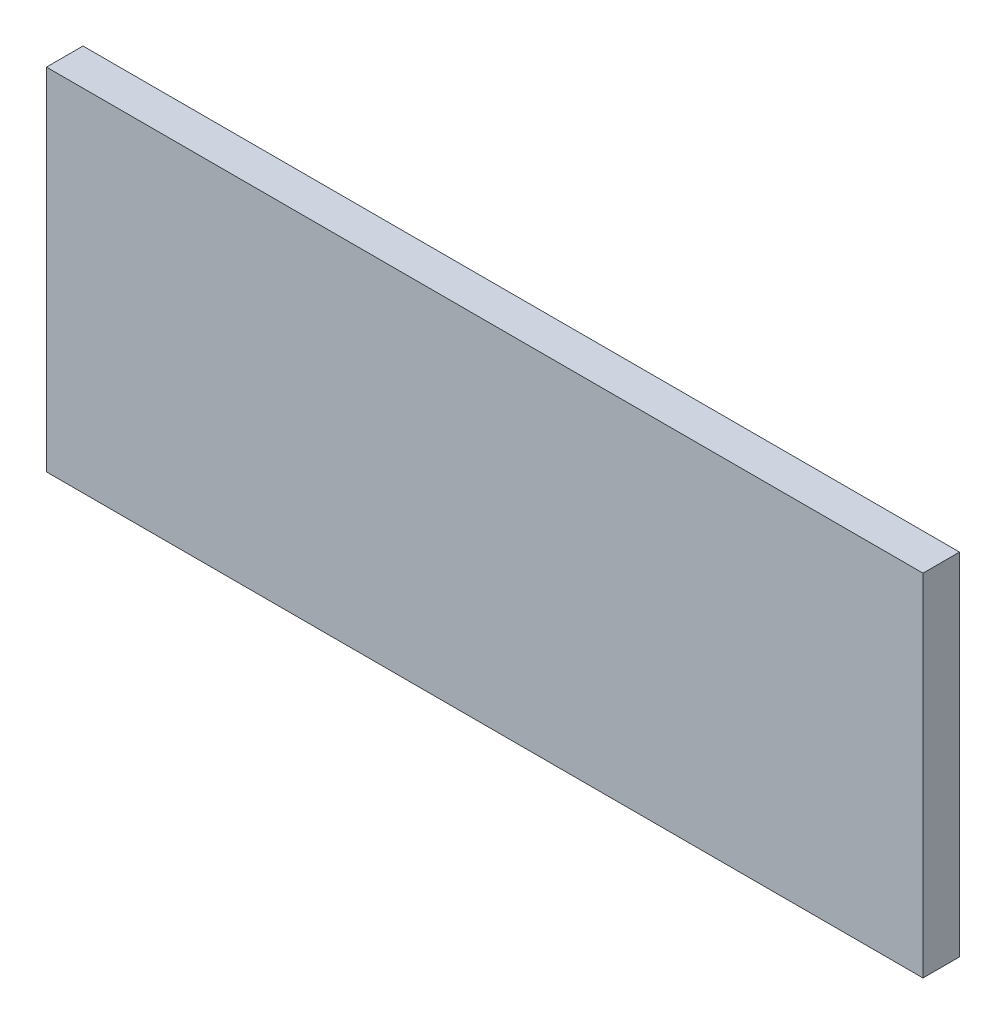
SolidWorks part; units mm, degrees
ref_plane "Front Plane" through (0, 0, 0) normal (0, 0, 1) x (1, 0, 0)
ref_plane "Top Plane" through (0, 0, 0) normal (0, 1, 0) x (1, 0, 0)
ref_plane "Right Plane" through (0, 0, 0) normal (1, 0, 0) x (0, 0, -1)
sketch "Sketch1" plane through (0, 0, 0) normal (0, 0, 1) x (1, 0, 0)
  line L1 (0, 0) -> (-76.2, 0)
  line L2 (0, 0) -> (0, 30.48)
  line L3 (0, 30.48) -> (-76.2, 30.48)
  line L4 (-76.2, 0) -> (-76.2, 30.48)
  point P5 (0, 0)
  dimension "D1" = 30.48
  dimension "D2" = 76.2
extrude "Boss-Extrude1" add sketch "Sketch1" along normal blind 3.175
